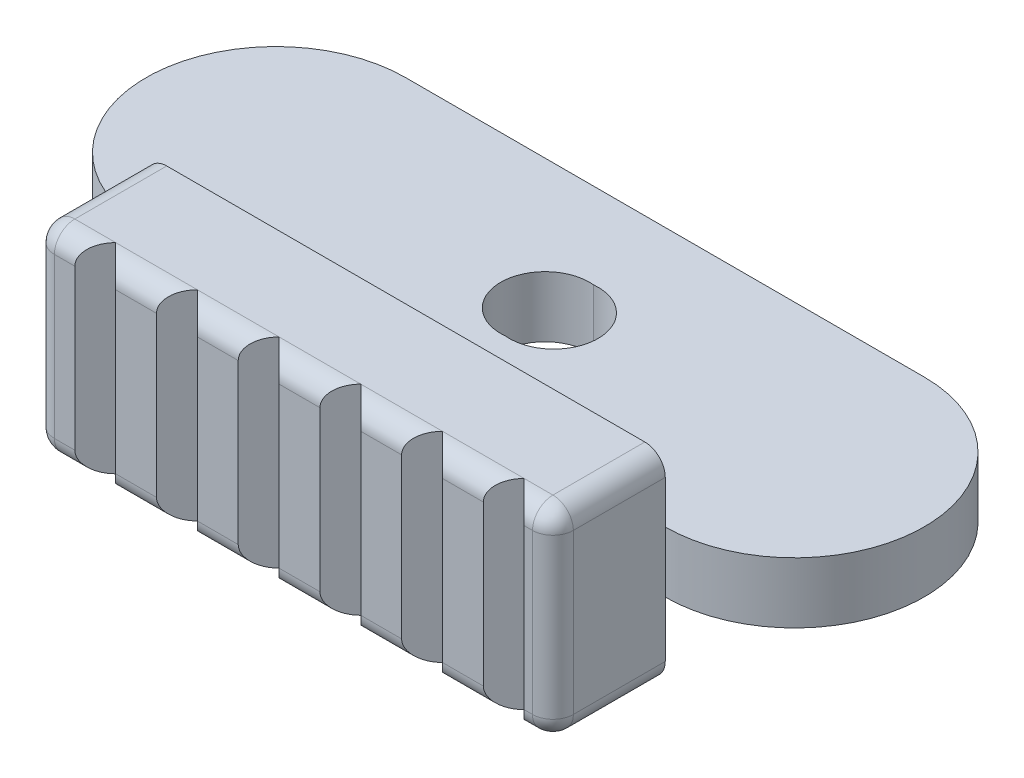
SolidWorks part; units mm, degrees
material "PET"
ref_plane "Front" through (0, 0, 0) normal (0, 0, 1) x (1, 0, 0)
ref_plane "Top" through (0, 0, 0) normal (0, 1, 0) x (1, 0, 0)
ref_plane "Right" through (0, 0, 0) normal (1, 0, 0) x (0, 0, -1)
sketch "Sketch1" plane through (0, 0, 0) normal (0, 1, 0) x (1, 0, 0)
  line L1 (-23.1719, 5.6259) -> (2.2281, 5.6259)
  line L3 (-23.1719, -7.0741) -> (2.2281, -7.0741)
  line L5 (-23.1719, 5.6259) -> (2.2281, -7.0741) construction
  line L6 (-23.1719, -7.0741) -> (2.2281, 5.6259) construction
  arc A0 (-23.1719, 5.6259) -> (-23.1719, -7.0741) centre (-23.1719, -0.7241) ccw
  arc A1 (2.2281, 5.6259) -> (2.2281, -7.0741) centre (2.2281, -0.7241) cw
  point P4 (-10.4719, -0.7241)
  dimension "D1" = 6.35
  dimension "D2" = 25.4
  dimension "D3" = 12.7
extrude "Boss-Extrude1" add sketch "Sketch1" along normal blind 2.975
sketch "Sketch2" plane through (0, 0, 7.0741) normal (0, 0, 1) x (1, 0, 0)
  line L1 (-23.1639, 6.0803) -> (2.2435, 6.0803)
  line L2 (-23.1639, 6.0803) -> (-23.1639, -3.7231)
  line L3 (-23.1639, -3.7231) -> (2.2435, -3.7231)
  line L4 (2.2435, 6.0803) -> (2.2435, -3.7231)
  line L5 (-23.1639, 6.0803) -> (2.2435, -3.7231) construction
  line L6 (-23.1639, -3.7231) -> (2.2435, 6.0803) construction
  point P4 (-10.4602, 1.1786)
extrude "Boss-Extrude2" add sketch "Sketch2" along normal blind 5.5
sketch "Sketch4" plane through (0, -3.7231, 0) normal (0, -1, 0) x (1, 0, 0)
  line L0 (-21.1639, 12.5741) -> (-19.1639, 12.5741)
  line L3 (-23.1639, 12.5741) -> (2.2435, 12.5741) construction
  line L62 (-23.1639, 12.5741) -> (-23.1639, 7.0741) construction
  line L65 (-21.1639, 12.5741) -> (-20.1639, 11.5741)
  line L66 (-20.1639, 11.5741) -> (-19.1639, 12.5741)
  line L67 (-19.1639, 12.5741) -> (-17.1639, 12.5741)
  line L71 (-17.1639, 12.5741) -> (-15.1639, 12.5741)
  line L72 (-17.1639, 12.5741) -> (-16.1639, 11.5741)
  line L73 (-16.1639, 11.5741) -> (-15.1639, 12.5741)
  line L74 (-13.1639, 12.5741) -> (-11.1639, 12.5741)
  line L75 (-13.1639, 12.5741) -> (-12.1639, 11.5741)
  line L76 (-12.1639, 11.5741) -> (-11.1639, 12.5741)
  line L77 (-9.1639, 12.5741) -> (-7.1639, 12.5741)
  line L78 (-9.1639, 12.5741) -> (-8.1639, 11.5741)
  line L79 (-8.1639, 11.5741) -> (-7.1639, 12.5741)
  line L80 (-5.1639, 12.5741) -> (-3.1639, 12.5741)
  line L81 (-5.1639, 12.5741) -> (-4.1639, 11.5741)
  line L82 (-4.1639, 11.5741) -> (-3.1639, 12.5741)
  line L83 (-1.1639, 12.5741) -> (0.8361, 12.5741)
  line L84 (-1.1639, 12.5741) -> (-0.1639, 11.5741)
  line L85 (-0.1639, 11.5741) -> (0.8361, 12.5741)
  line M4 (2.2435, 12.5741) -> (-23.1639, 12.5741)
  dimension "D1" = 2
  dimension "D3" = 2
  dimension "D4" = 2
  dimension "D5" = 6
fillet "Fillet1" radius 1 1 edges at (-23.1639, 1.1786, 12.5741)
fillet "Fillet2" radius 1 1 edges at (2.2435, 1.1786, 12.5741)
fillet "Fillet3" radius 1 5 edges at (2.2435, -3.7231, 9.3241) (1.9506, -3.7231, 12.2812) (-10.4602, -3.7231, 12.5741) (-22.871, -3.7231, 12.2812) (-23.1639, -3.7231, 9.3241)
fillet "Fillet4" radius 1 5 edges at (-23.1639, 6.0803, 9.3241) (-22.871, 6.0803, 12.2812) (-10.4602, 6.0803, 12.5741) (1.9506, 6.0803, 12.2812) (2.2435, 6.0803, 9.3241)
sketch "Sketch5" plane through (0, 0, 0) normal (0, -1, 0) x (1, 0, 0)
  line L0 (-29.5219, 0.7241) -> (9.5439, 0.7241) construction
  line L1 (-9.989, 2.8991) -> (-9.989, -7.0151) construction
  arc A0 (-23.1719, 7.0741) -> (-23.1719, -5.6259) centre (-23.1719, 0.7241) ccw construction
  circle A1 centre (-9.989, 0.7241) radius 2.175
  arc A2 (2.2281, -5.6259) -> (2.2281, 7.0741) centre (2.2281, 0.7241) ccw construction
  dimension "D1" = 4.35
extrude "Cut-Extrude3" cut sketch "Sketch4" against normal blind 10 contours L72 L73 M4 | L75 L76 M4 | L78 L79 M4 | L81 L82 M4 | L84 L85 M4 | L0 L65 L66
sketch "Sketch6" plane through (0, 2.975, 0) normal (0, 1, 0) x (1, 0, 0)
  line L0 (-29.5219, -0.7241) -> (10.3848, -0.7241) construction
  line L1 (-9.5686, -6.8062) -> (-9.5686, 8.7083) construction
  arc A0 (-23.1719, 5.6259) -> (-23.1719, -7.0741) centre (-23.1719, -0.7241) ccw construction
  circle A1 centre (-9.5686, -0.7241) radius 2.175
  dimension "D1" = 4.35
extrude "Cut-Extrude4" cut sketch "Sketch6" against normal blind 10
extrude "Cut-Extrude2" cut sketch "Sketch5" against normal blind 10 contours A1
